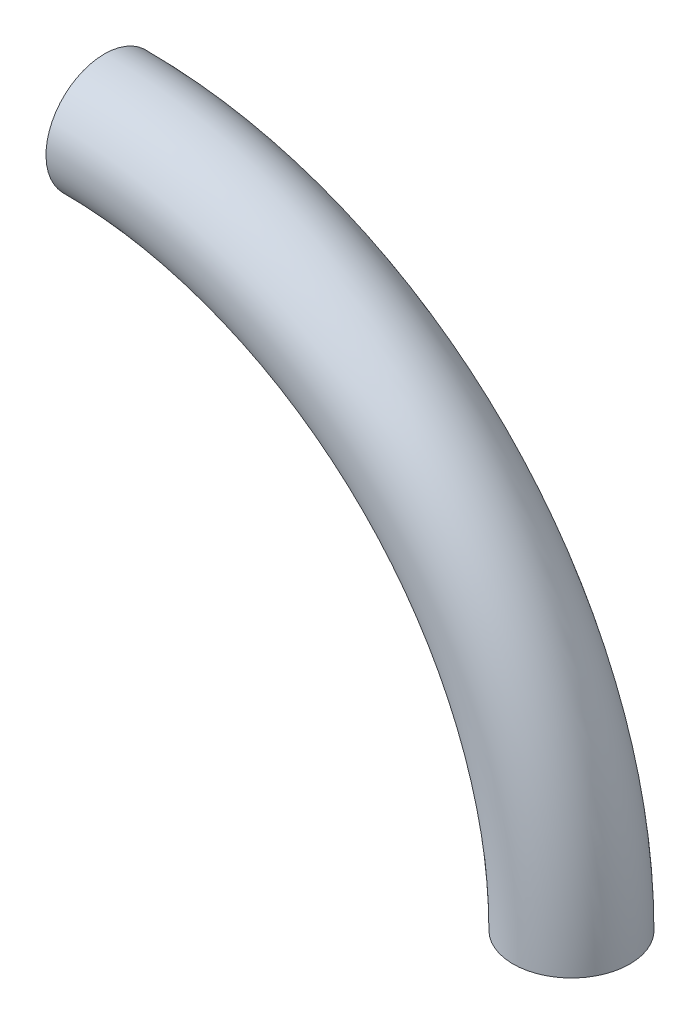
SolidWorks part; units mm, degrees
material "Copper"
ref_plane "Front Plane" through (0, 0, 0) normal (0, 0, 1) x (1, 0, 0)
ref_plane "Top Plane" through (0, 0, 0) normal (0, 1, 0) x (1, 0, 0)
ref_plane "Right Plane" through (0, 0, 0) normal (1, 0, 0) x (0, 0, -1)
sketch "Sketch1" plane through (0, 0, 0) normal (0, 0, 1) x (1, 0, 0)
  arc A0 (0, 0) -> (25.4, -25.4) centre (0, -25.4) cw
  dimension "D1" = 25.4
  dimension "D2" = 25.4
ref_plane "Plane1" through (25.4, -25.4, 0) normal (0, -1, 0) x (-1, 0, 0)
sketch "Sketch2" plane through (25.4, -25.4, 0) normal (0, -1, 0) x (-1, 0, 0)
  circle A0 centre (0, 0) radius 2.159
  circle A1 centre (0, 0) radius 3.175
  dimension "D1" = 4.318
  dimension "D2" = 6.35
sweep "Sweep1" add profiles "Sketch2" path "Sketch1"
